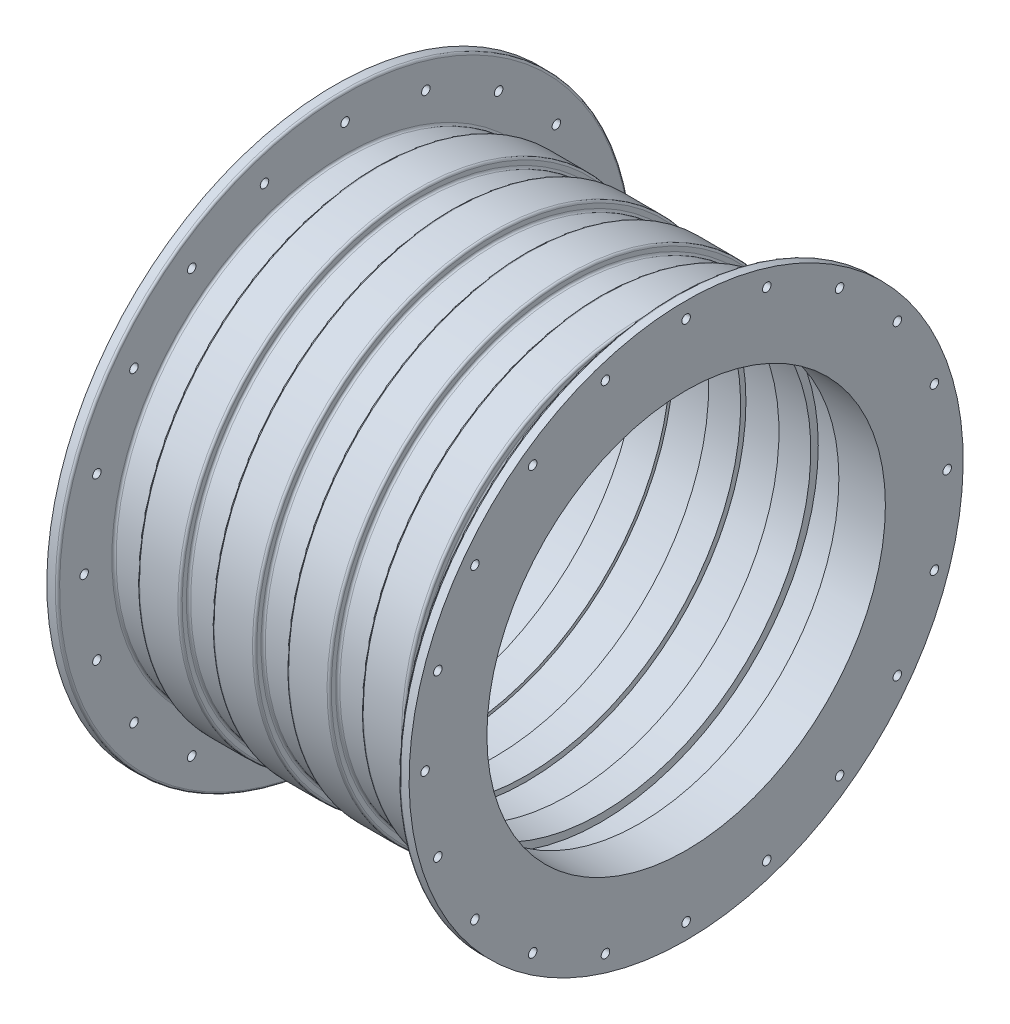
SolidWorks part; units mm, degrees
ref_plane "Front Plane" through (0, 0, 0) normal (0, 0, 1) x (1, 0, 0)
ref_plane "Top Plane" through (0, 0, 0) normal (0, 1, 0) x (1, 0, 0)
ref_plane "Right Plane" through (0, 0, 0) normal (1, 0, 0) x (0, 0, -1)
sketch "Sketch1" plane through (0, 0, 0) normal (0, 0, 1) x (1, 0, 0)
  line L0 (-34.0909, 0) -> (34.0909, 0) construction
  line L2 (75.5, 130) -> (70.5, 130)
  line L3 (70.5, 130) -> (70.5, 108.5)
  line L4 (70.5, 108.5) -> (55.5, 108.5)
  line L5 (55.5, 108.5) -> (55.5, 112.5)
  line L6 (55.5, 112.5) -> (35.5, 112.5)
  line L7 (35.5, 112.5) -> (35.5, 108.5)
  line L8 (35.5, 108.5) -> (20.5, 108.5)
  line L9 (20.5, 108.5) -> (20.5, 112.5)
  line L10 (20.5, 112.5) -> (0.5, 112.5)
  line L11 (0.5, 112.5) -> (0.5, 108.5)
  line L12 (0.5, 108.5) -> (-14.5, 108.5)
  line L13 (-14.5, 108.5) -> (-14.5, 112.5)
  line L14 (-14.5, 112.5) -> (-34.5, 112.5)
  line L15 (-34.5, 112.5) -> (-34.5, 108.5)
  line L16 (-34.5, 108.5) -> (-49.5, 108.5)
  line L17 (-49.5, 108.5) -> (-49.5, 112.5)
  line L18 (-49.5, 112.5) -> (-69.5, 112.5)
  line L19 (-69.5, 112.5) -> (-69.5, 108.5)
  line L20 (-69.5, 108.5) -> (-84.5, 108.5)
  line L21 (-84.5, 108.5) -> (-84.5, 135)
  line L22 (-84.5, 135) -> (-89.5, 135)
  line L23 (-89.5, 135) -> (-89.5, 101.5)
  line L24 (-89.5, 101.5) -> (-69.5, 101.5)
  line L25 (-69.5, 101.5) -> (-69.5, 105)
  line L26 (-69.5, 105) -> (-49.4356, 105)
  line L27 (-49.4356, 105) -> (-49.4356, 102.5)
  line L28 (-49.4356, 102.5) -> (-34.4356, 102.5)
  line L29 (-34.4356, 102.5) -> (-34.4356, 104)
  line L30 (-34.4356, 104) -> (-14.4356, 104)
  line L31 (-14.4356, 104) -> (-14.4356, 100.5)
  line L32 (-14.4356, 100.5) -> (0.5644, 100.5)
  line L33 (0.5644, 100.5) -> (0.5644, 103)
  line L34 (0.5644, 103) -> (20.5644, 103)
  line L35 (20.5644, 103) -> (20.5644, 98.5)
  line L36 (20.5644, 98.5) -> (35.5, 98.5)
  line L37 (35.5, 98.5) -> (35.5, 102)
  line L38 (35.5, 102) -> (53.6682, 102)
  line L39 (53.6682, 102) -> (53.6682, 93.5)
  line L40 (53.6682, 93.5) -> (75.5, 93.5)
  line L43 (75.5, 93.5) -> (75.5, 130)
  point P3 (0, 0)
  point P4 (0, 0)
  point P6 (-49.5, 110.5)
  point P47 (-12.3829, 150.0438)
  point P48 (-26.7007, 122.43)
  dimension "D1" = 5
  dimension "D2" = 5
  dimension "D3" = 15
  dimension "D4" = 15
  dimension "D5" = 20
  dimension "D6" = 7
  dimension "D7" = 135
  dimension "D8" = 130
  dimension "D9" = 15
  dimension "D10" = 102
  dimension "D11" = 10
  dimension "D12" = 103
  dimension "D13" = 101.5
  dimension "D14" = 6
  dimension "D15" = 8
  dimension "D16" = 104
  dimension "D17" = 4
  dimension "D18" = 89.5
  dimension "D19" = 105
revolve "Revolve1" add sketch "Sketch1" angle 360 about L0
sketch "Sketch2" plane through (-89.5, 0, 0) normal (-1, 0, 0) x (0, 0, 1)
  circle A0 centre (0, 122.5) radius 2
  dimension "D1" = 4
  dimension "D2" = 122.5
extrude "Cut-Extrude1" cut sketch "Sketch2" against normal blind 10
sketch "Sketch3" plane through (75.5, 0, 0) normal (1, 0, 0) x (0, 0, -1)
  circle A0 centre (0, 122.5) radius 2
  dimension "D2" = 4
  dimension "D1" = 122.5
extrude "Cut-Extrude2" cut sketch "Sketch3" against normal blind 10
pattern_circular "CirPattern1" count 20 over 360 about axis through (0, 0, 0) along (1, 0, 0) of "Cut-Extrude2", "Cut-Extrude1"
fillet "Fillet1" radius 1 19 edges at (-84.5, -108.5, 0) (70.5, -108.5, 0) (55.5, -108.5, 0) (55.5, -112.5, 0) (35.5, -112.5, 0) (35.5, -108.5, 0) (20.5, -108.5, 0) (20.5, -112.5, 0) (0.5, -112.5, 0) (0.5, -108.5, 0) (-14.5, -108.5, 0) (-14.5, -112.5, 0) (-34.5, -112.5, 0) (-34.5, -108.5, 0) (-49.5, -108.5, 0) (-49.5, -112.5, 0) (-69.5, -112.5, 0) (70.5, -130, 0) (-84.5, -135, 0)
